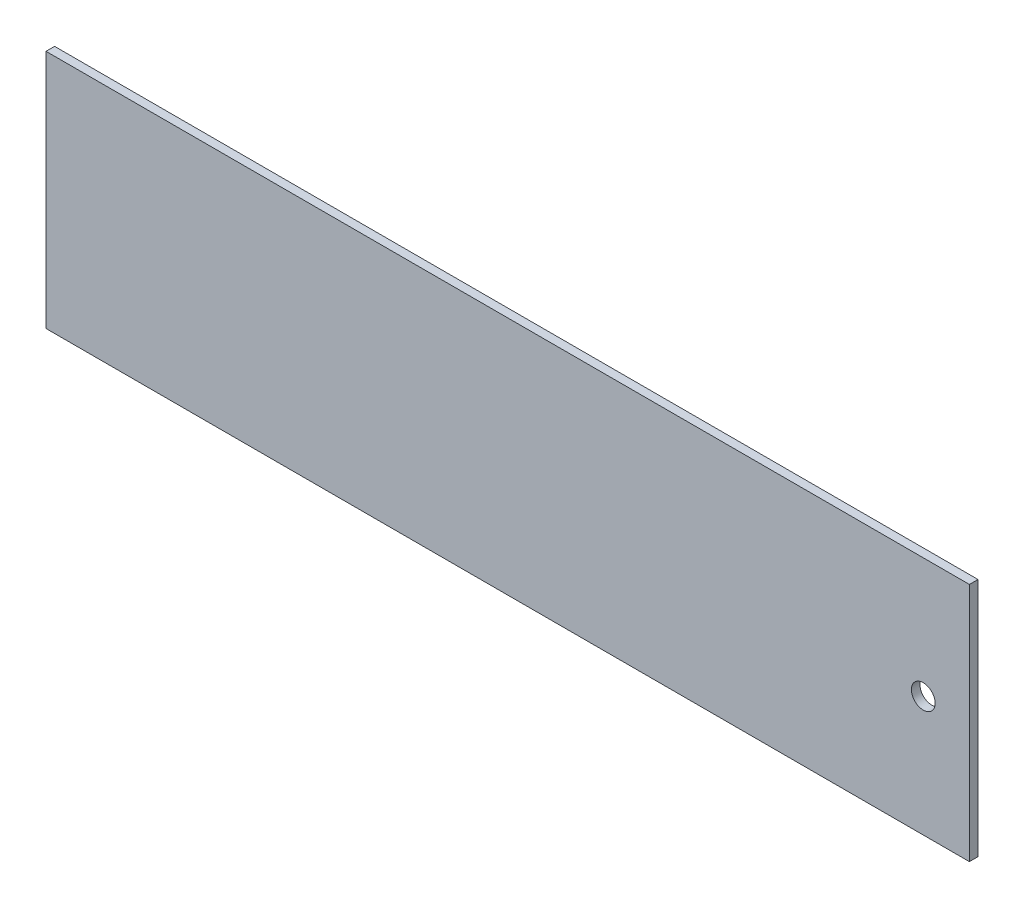
SolidWorks part; units mm, degrees
ref_plane "Front Plane" through (0, 0, 0) normal (0, 0, 1) x (1, 0, 0)
ref_plane "Top Plane" through (0, 0, 0) normal (0, 1, 0) x (1, 0, 0)
ref_plane "Right Plane" through (0, 0, 0) normal (1, 0, 0) x (0, 0, -1)
sketch "Sketch2" plane through (0, 0, 0) normal (0, 0, 1) x (1, 0, 0)
  line L1 (0, 0) -> (-254, 0)
  line L2 (0, 0) -> (0, 66.04)
  line L3 (0, 66.04) -> (-254, 66.04)
  line L4 (-254, 0) -> (-254, 66.04)
  dimension "D1" = 66.04
  dimension "D2" = 254
extrude "Boss-Extrude1" add sketch "Sketch2" along normal blind 2.3622
sketch "Sketch3" plane through (0, 0, 2.3622) normal (0, 0, 1) x (1, 0, 0)
  line L0 (0, 0) -> (0, 66.04) construction
  circle A0 centre (-12.7, 33.02) radius 3.2639
  point P2 (0, 33.02)
  dimension "D2" = 6.5278
  dimension "D1" = 12.7
extrude "Cut-Extrude1" cut sketch "Sketch3" against normal through all
